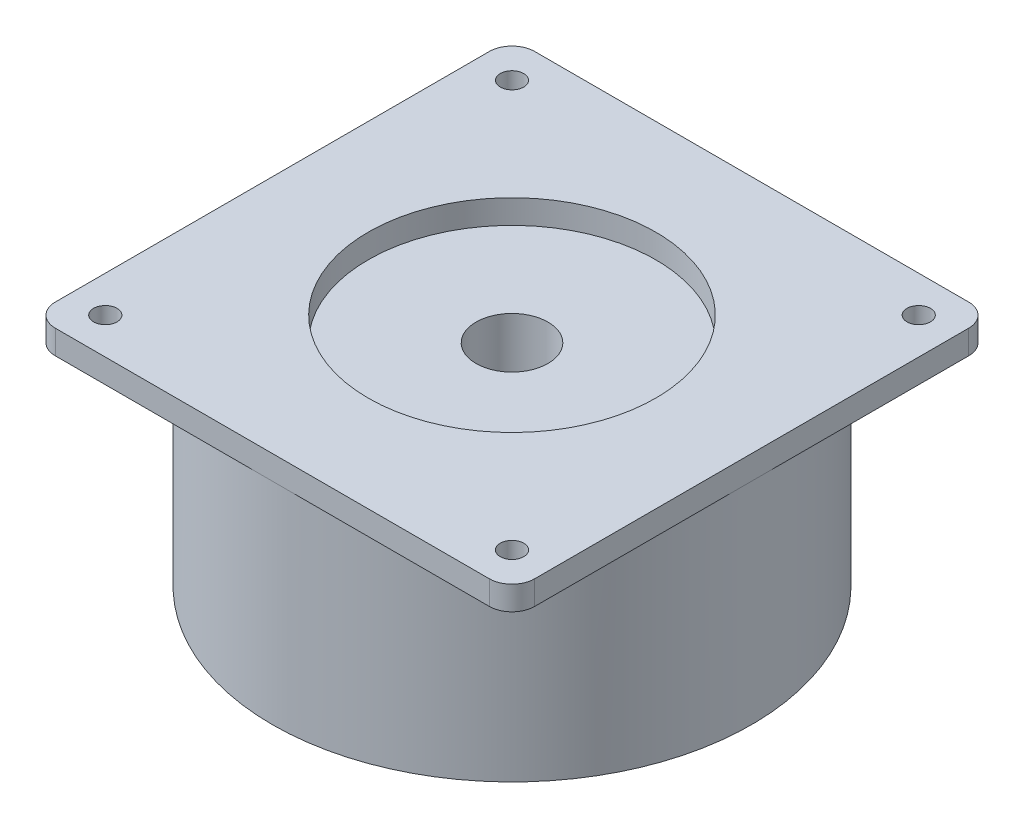
SolidWorks part; units mm, degrees
ref_plane "Front Plane" through (0, 0, 0) normal (0, 0, 1) x (1, 0, 0)
ref_plane "Top Plane" through (0, 0, 0) normal (0, 1, 0) x (1, 0, 0)
ref_plane "Right Plane" through (0, 0, 0) normal (1, 0, 0) x (0, 0, -1)
sketch "Sketch1" plane through (0, 0, 0) normal (0, 1, 0) x (1, 0, 0)
  circle A0 centre (0, 0) radius 31.75
  circle A1 centre (0, 0) radius 4.7625
extrude "Boss-Extrude1" add sketch "Sketch1" along normal blind 27.94
sketch "Sketch2" plane through (0, 27.94, 0) normal (0, 1, 0) x (1, 0, 0)
  line L1 (-28.75, 31.75) -> (28.75, 31.75)
  line L2 (-31.75, 28.75) -> (-31.75, -28.75)
  line L3 (-28.75, -31.75) -> (28.75, -31.75)
  line L4 (31.75, 28.75) -> (31.75, -28.75)
  line L5 (-31.75, 31.75) -> (31.75, -31.75) construction
  line L6 (-31.75, -31.75) -> (31.75, 31.75) construction
  arc A0 (-31.75, -28.75) -> (-28.75, -31.75) centre (-28.75, -28.75) ccw
  arc A1 (28.75, -31.75) -> (31.75, -28.75) centre (28.75, -28.75) ccw
  arc A2 (31.75, 28.75) -> (28.75, 31.75) centre (28.75, 28.75) ccw
  arc A3 (-31.75, 28.75) -> (-28.75, 31.75) centre (-28.75, 28.75) cw
  circle A5 centre (-26.9408, 26.9408) radius 1.5557
  circle A6 centre (26.9408, 26.9408) radius 1.5558
  circle A7 centre (26.9408, -26.9408) radius 1.5558
  circle A8 centre (-26.9408, -26.9408) radius 1.5558
  point P0 (0, 0)
  point P31 (0, 0)
  dimension "D3" = 3
  dimension "D4" = 4
  dimension "D1" = 63.5
  dimension "D2" = 63.5
extrude "Boss-Extrude2" add sketch "Sketch2" along normal blind 3.175
sketch "Sketch3" plane through (0, 31.115, 0) normal (0, 1, 0) x (1, 0, 0)
  circle A0 centre (0, 0) radius 19.05
extrude "Cut-Extrude1" cut sketch "Sketch3" against normal blind 3.175
